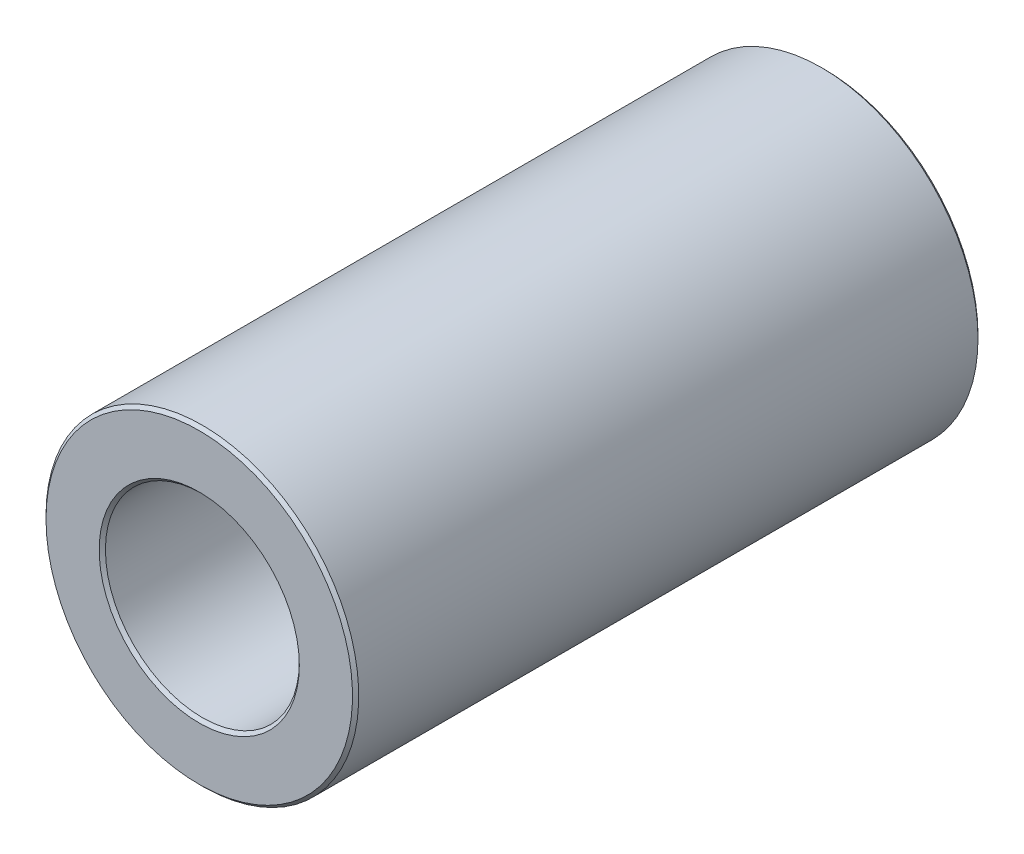
SolidWorks part; units mm, degrees
material "6061 合金"
ref_plane "前视基准面" through (0, 0, 0) normal (0, 0, 1) x (1, 0, 0)
ref_plane "上视基准面" through (0, 0, 0) normal (0, 1, 0) x (1, 0, 0)
ref_plane "右视基准面" through (0, 0, 0) normal (1, 0, 0) x (0, 0, -1)
other "Configuration Table"
sketch "草图1" plane through (0, 0, 0) normal (0, 0, 1) x (1, 0, 0)
  circle A0 centre (0, 0) radius 1.55
  circle A1 centre (0, 0) radius 2.5
  dimension "D1" = 3.1
  dimension "D2" = 5
extrude "凸台-拉伸1" add sketch "草图1" along normal mid plane 10
chamfer "倒角1" distance 0.05 angle 45 4 edges at (1.55, 0, -5) (2.5, 0, -5) (2.5, 0, 5) (1.55, 0, 5)
